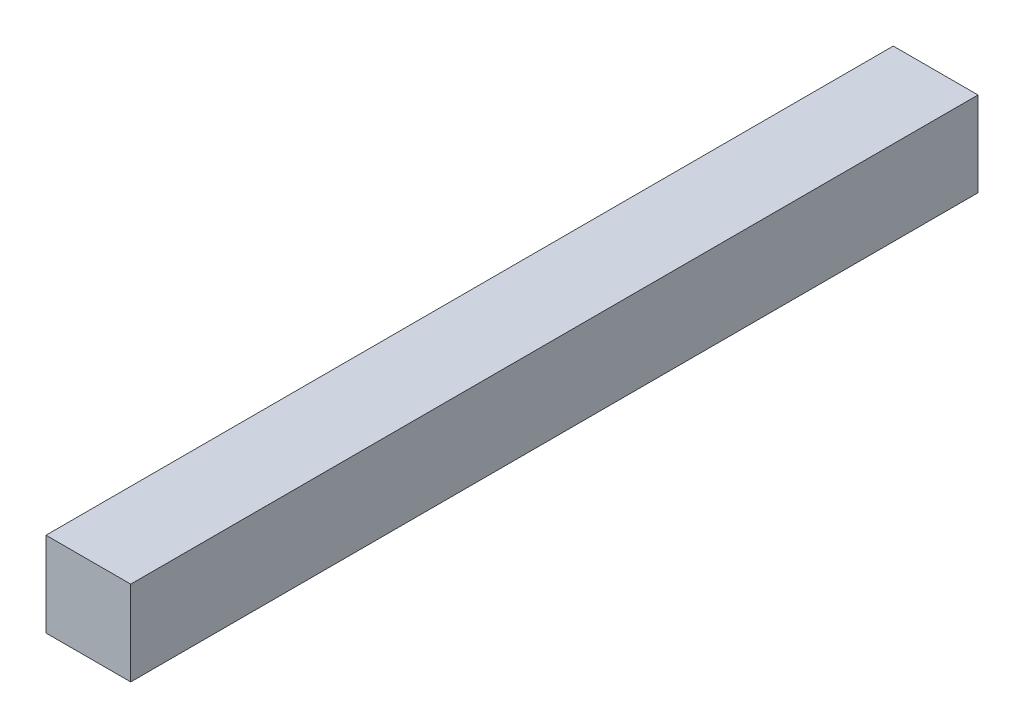
SolidWorks part; units mm, degrees
ref_plane "Front Plane" through (0, 0, 0) normal (0, 0, 1) x (1, 0, 0)
ref_plane "Top Plane" through (0, 0, 0) normal (0, 1, 0) x (1, 0, 0)
ref_plane "Right Plane" through (0, 0, 0) normal (1, 0, 0) x (0, 0, -1)
sketch "Sketch1" plane through (0, 0, 0) normal (0, 0, 1) x (1, 0, 0)
  line L1 (-6.6589, 2.3467) -> (3.3411, 2.3467)
  line L2 (-6.6589, 2.3467) -> (-6.6589, 12.3467)
  line L3 (-6.6589, 12.3467) -> (3.3411, 12.3467)
  line L4 (3.3411, 2.3467) -> (3.3411, 12.3467)
  dimension "D1" = 10
  dimension "D2" = 10
extrude "Boss-Extrude1" add sketch "Sketch1" along normal blind 100
